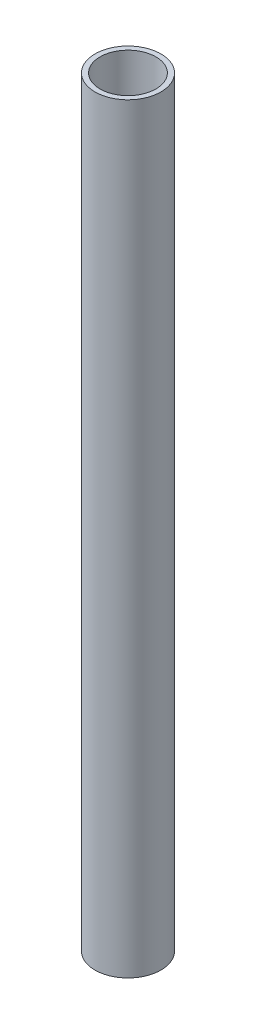
SolidWorks part; units mm, degrees
ref_plane "Спереди" through (0, 0, 0) normal (0, 0, 1) x (1, 0, 0)
ref_plane "Сверху" through (0, 0, 0) normal (0, 1, 0) x (1, 0, 0)
ref_plane "Справа" through (0, 0, 0) normal (1, 0, 0) x (0, 0, -1)
other "Configuration Table"
sketch "Sketch1" plane through (0, 0, 0) normal (0, 1, 0) x (1, 0, 0)
  circle A0 centre (0, 0) radius 13
  circle A1 centre (0, 0) radius 11
  dimension "D1" = 26
  dimension "D2" = 2
extrude "Boss-Extrude1" add sketch "Sketch1" along normal mid plane 300
